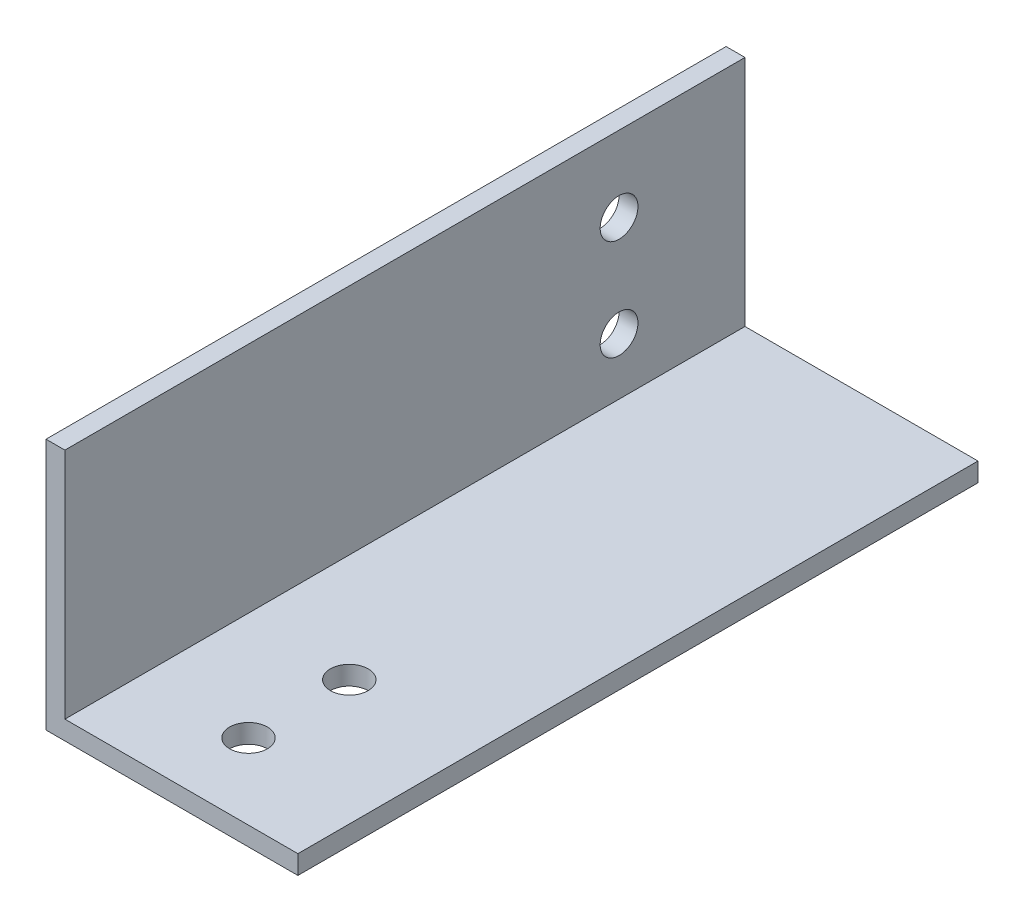
SolidWorks part; units mm, degrees
ref_plane "Plan de face" through (0, 0, 0) normal (0, 0, 1) x (1, 0, 0)
ref_plane "Plan de dessus" through (0, 0, 0) normal (0, 1, 0) x (1, 0, 0)
ref_plane "Plan de droite" through (0, 0, 0) normal (1, 0, 0) x (0, 0, -1)
sketch "Esquisse1" plane through (0, 0, 0) normal (0, 0, 1) x (1, 0, 0)
  line L0 (-18.7143, 3.4981) -> (-18.7143, -16.5019)
  line L1 (-18.7143, -16.5019) -> (1.2857, -16.5019)
  line L2 (1.2857, -16.5019) -> (1.2857, -15.0019)
  line L3 (1.2857, -15.0019) -> (-17.2143, -15.0019)
  line L4 (-17.2143, -15.0019) -> (-17.2143, 3.4981)
  line L5 (-17.2143, 3.4981) -> (-18.7143, 3.4981)
  dimension "D1" = 1.5
  dimension "D2" = 1.5
  dimension "D3" = 20
  dimension "D4" = 20
extrude "Extrusion1" add sketch "Esquisse1" along normal blind 54
sketch "Esquisse2" plane through (0, -15.0019, 0) normal (0, 1, 0) x (-1, 0, 0)
  line L0 (-1.2857, 54) -> (17.2143, 54) construction
  circle A0 centre (8.6337, 48) radius 1.5
  circle A1 centre (8.6337, 40) radius 1.5
  dimension "D1" = 8
  dimension "D2" = 6
extrude "Extrusion2" cut sketch "Esquisse2" against normal blind 20
sketch "Esquisse3" plane through (-18.7143, 0, 0) normal (-1, 0, 0) x (0, 0, 1)
  line L0 (54, 3.4981) -> (0, 3.4981) construction
  line L1 (10, -2.5019) -> (10, -10.5019) construction
  line L2 (0, 3.4981) -> (0, -16.5019) construction
  circle A0 centre (10, -2.5019) radius 1.5
  circle A1 centre (10, -10.5019) radius 1.5
  point P6 (0, -6.5019)
  dimension "D1" = 8
  dimension "D2" = 6
  dimension "D3" = 10
extrude "Extrusion3" cut sketch "Esquisse3" against normal blind 10
